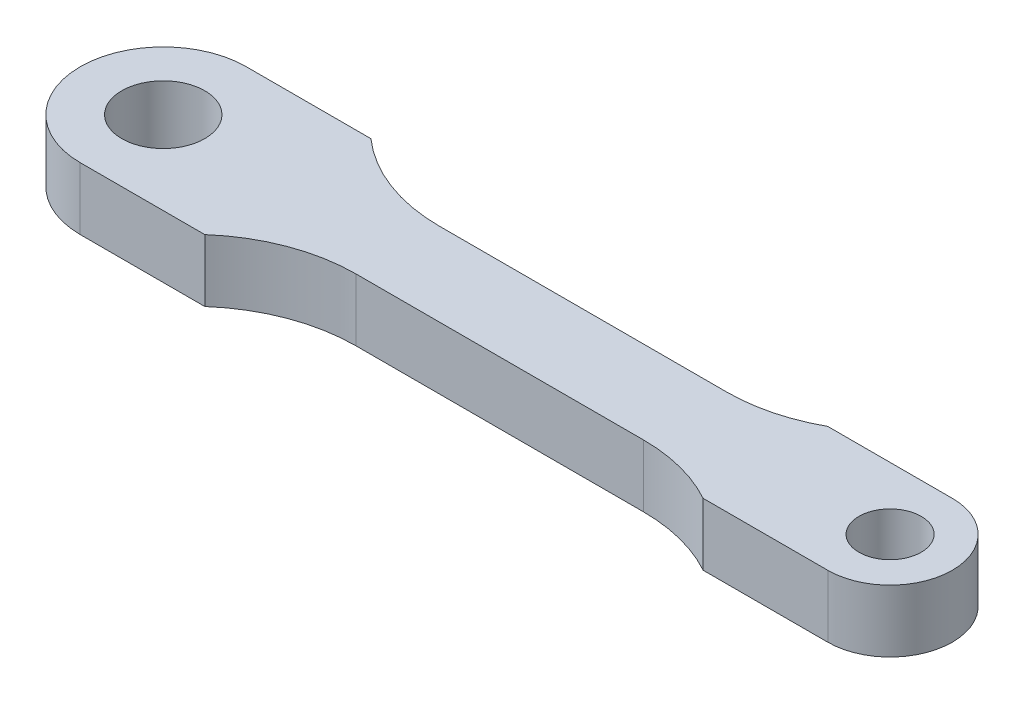
SolidWorks part; units mm, degrees
ref_plane "Front Plane" through (0, 0, 0) normal (0, 0, 1) x (1, 0, 0)
ref_plane "Top Plane" through (0, 0, 0) normal (0, 1, 0) x (1, 0, 0)
ref_plane "Right Plane" through (0, 0, 0) normal (1, 0, 0) x (0, 0, -1)
sketch "Sketch2" plane through (0, 0, 0) normal (0, 1, 0) x (1, 0, 0)
  line L0 (-17.5, 0) -> (17.5, 0) construction
  line L1 (-17.5, 4) -> (-11.5, 4)
  line L2 (17.5, 3) -> (11.5, 3)
  line L3 (-6.2085, 2) -> (7.627, 2)
  line L4 (17.5, -3) -> (11.5, -3)
  line L5 (-6.2085, -2) -> (7.627, -2)
  line L6 (-17.5, -4) -> (-11.5, -4)
  circle A0 centre (-17.5, 0) radius 4
  circle A1 centre (17.5, 0) radius 3
  arc A2 (-6.2085, 2) -> (-11.5, 4) centre (-6.2085, 10) cw
  arc A3 (7.627, 2) -> (11.5, 3) centre (7.627, 10) ccw
  arc A4 (-6.2085, -2) -> (-11.5, -4) centre (-6.2085, -10) ccw
  arc A5 (7.627, -2) -> (11.5, -3) centre (7.627, -10) cw
  circle A6 centre (-17.5, 0) radius 2
  circle A7 centre (17.5, 0) radius 1.5
  dimension "D1" = 8
  dimension "D2" = 6
  dimension "D7" = 8
  dimension "D8" = 8
  dimension "D9" = 4
  dimension "D10" = 3
  dimension "D3" = 35
  dimension "D4" = 6
  dimension "D5" = 6
  dimension "D6" = 4
extrude "Boss-Extrude1" add sketch "Sketch2" along normal mid plane 3
